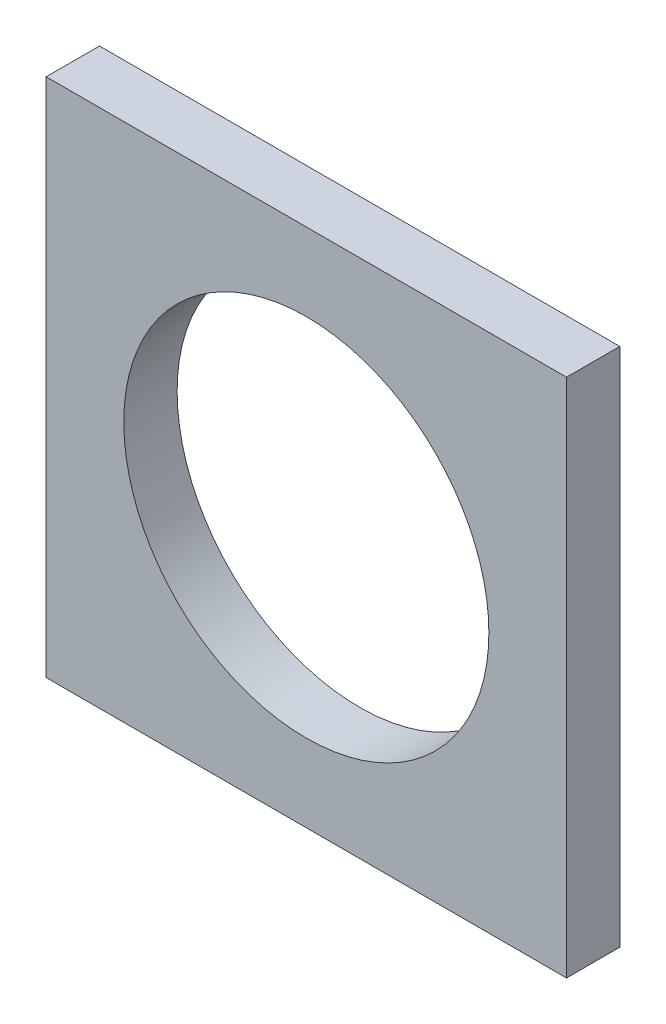
SolidWorks part; units mm, degrees
ref_plane "Front Plane" through (0, 0, 0) normal (0, 0, 1) x (1, 0, 0)
ref_plane "Top Plane" through (0, 0, 0) normal (0, 1, 0) x (1, 0, 0)
ref_plane "Right Plane" through (0, 0, 0) normal (1, 0, 0) x (0, 0, -1)
sketch "Sketch1" plane through (0, 0, 0) normal (0, 0, 1) x (1, 0, 0)
  line L1 (0, 0) -> (30.988, 0)
  line L2 (0, 0) -> (0, 30.988)
  line L3 (0, 30.988) -> (30.988, 30.988)
  line L4 (30.988, 0) -> (30.988, 30.988)
  circle A0 centre (15.494, 15.494) radius 10.8331
  circle A1 centre (15.494, 15.494) radius 5.7277
  dimension "D5" = 21.6662
  dimension "D6" = 11.4554
  dimension "D1" = 30.988
  dimension "D2" = 30.988
  dimension "D3" = 15.494
  dimension "D4" = 15.494
extrude "Boss-Extrude1" add sketch "Sketch1" along normal blind 3.175 contours L2 L1 L4 L3 | A1
sketch "Sketch2" plane through (0, 0, 0) normal (0, 0, -1) x (-1, 0, 0)
  circle A0 centre (-15.494, 15.494) radius 10.8712
  dimension "D1" = 21.7424
extrude "Cut-Extrude2" cut sketch "Sketch2" against normal blind 3.2512
equation "\"D3@Sketch1\"=\"D1@Sketch1\"/2"
equation "\"D4@Sketch1\"=\"D2@Sketch1\"/2"
